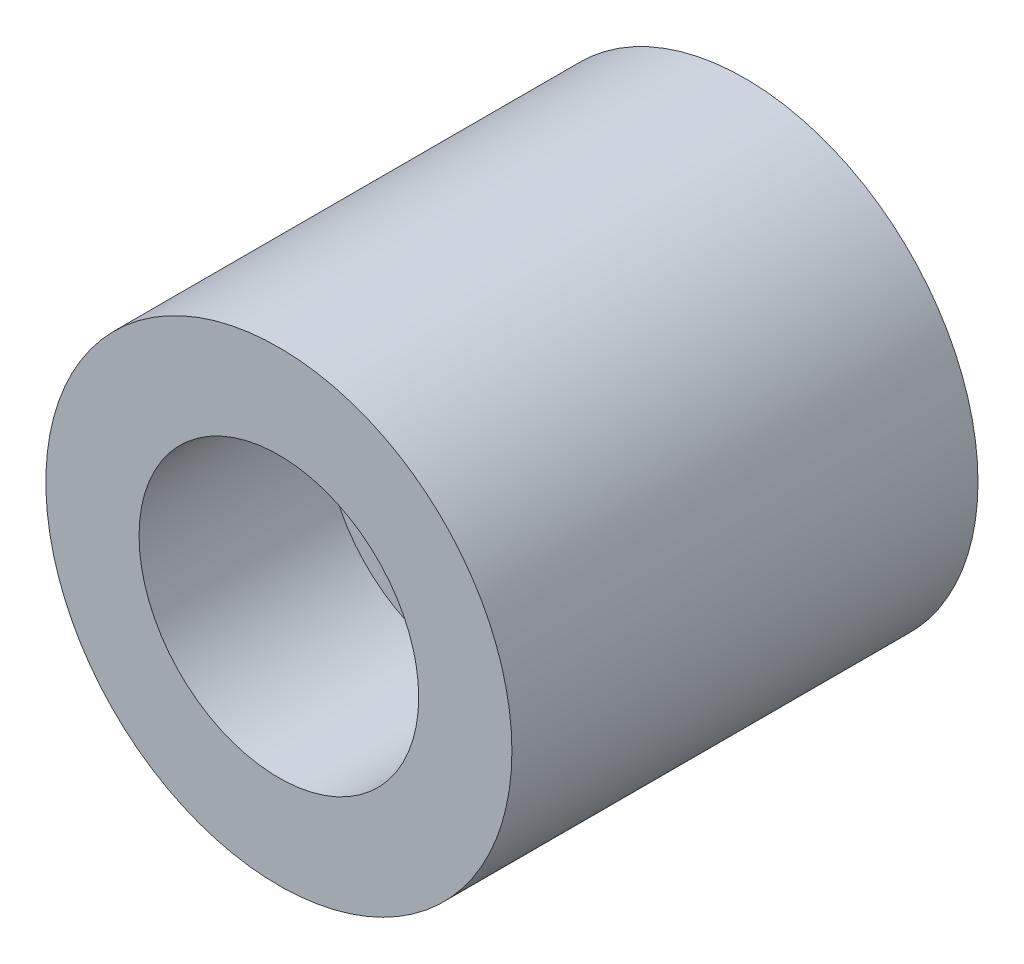
SolidWorks part; units mm, degrees
ref_plane "Front Plane" through (0, 0, 0) normal (0, 0, 1) x (1, 0, 0)
ref_plane "Top Plane" through (0, 0, 0) normal (0, 1, 0) x (1, 0, 0)
ref_plane "Right Plane" through (0, 0, 0) normal (1, 0, 0) x (0, 0, -1)
ref_plane "plane:base-xy" through (0, 0, 0) normal (0, 0, 1) x (1, 0, 0)
sketch "sketch:base-profile" plane through (0, 0, 0) normal (0, 0, 1) x (1, 0, 0)
  circle A0 centre (0, 0) radius 10
extrude "feature:base" add sketch "sketch:base-profile" along normal blind 20 separate body
ref_plane "plane:top-xy" through (0, 0, 20) normal (0, 0, 1) x (1, 0, 0)
sketch "sketch:bore-profile" plane through (0, 0, 20) normal (0, 0, 1) x (1, 0, 0)
  circle A0 centre (0, 0) radius 3
extrude "feature:bore" cut sketch "sketch:bore-profile" against normal through all
sketch "sketch:counterbore-profile" plane through (0, 0, 20) normal (0, 0, 1) x (1, 0, 0)
  circle A0 centre (0, 0) radius 6
extrude "feature:counterbore" cut sketch "sketch:counterbore-profile" against normal blind 8
